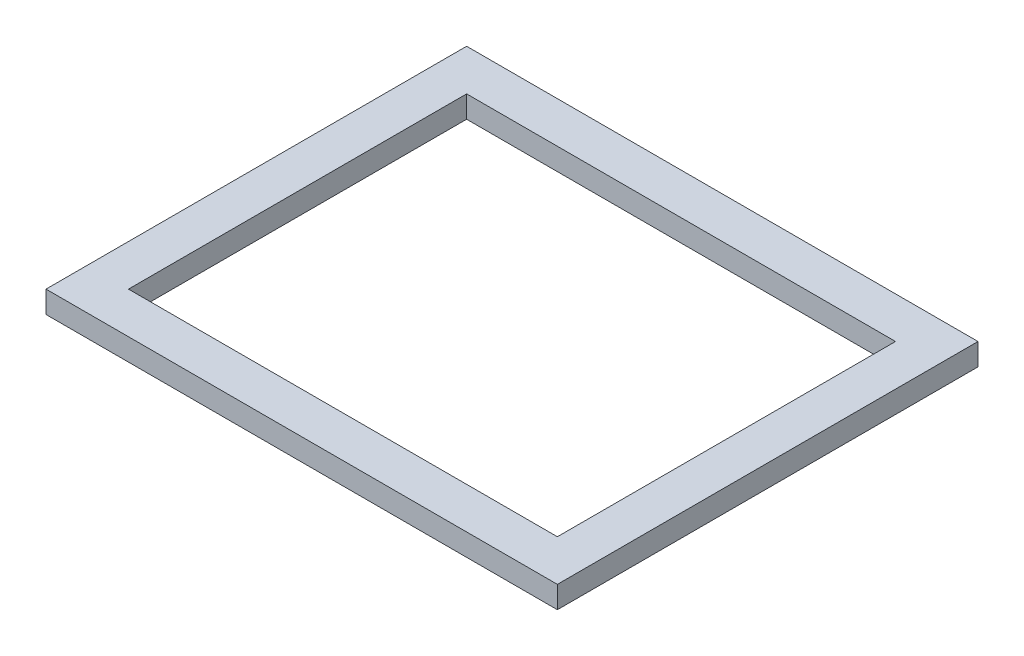
SolidWorks part; units mm, degrees
ref_plane "Front Plane" through (0, 0, 0) normal (0, 0, 1) x (1, 0, 0)
ref_plane "Top Plane" through (0, 0, 0) normal (0, 1, 0) x (1, 0, 0)
ref_plane "Right Plane" through (0, 0, 0) normal (1, 0, 0) x (0, 0, -1)
sketch "Sketch1" plane through (0, 0, 0) normal (0, 1, 0) x (1, 0, 0)
  line L1 (-9.3, 7.65) -> (9.3, 7.65)
  line L2 (-9.3, 7.65) -> (-9.3, -7.65)
  line L3 (-9.3, -7.65) -> (9.3, -7.65)
  line L4 (9.3, 7.65) -> (9.3, -7.65)
  line L5 (-9.3, 7.65) -> (9.3, -7.65) construction
  line L6 (-9.3, -7.65) -> (9.3, 7.65) construction
  point P4 (0, 0)
  point P5 (0, 0)
  dimension "D1" = 18.6
  dimension "D2" = 15.3
extrude "Extrude-Thin1" add sketch "Sketch1" along normal blind 0.8 thin contours L1 L4 L3 L2
